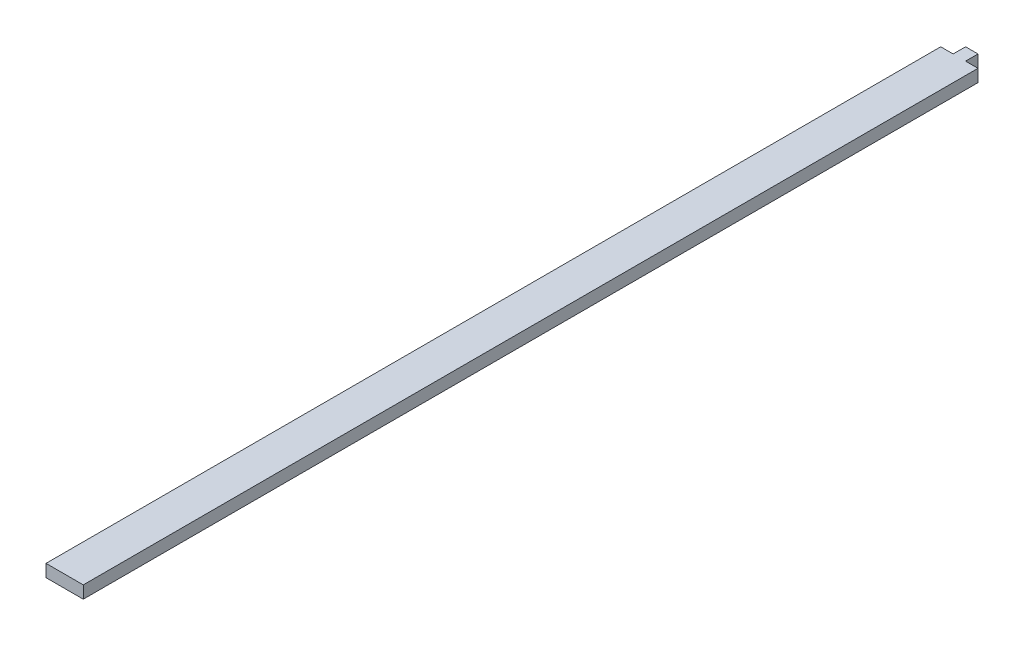
SolidWorks part; units mm, degrees
material "Mahogany"
ref_plane "Front" through (0, 0, 0) normal (0, 0, 1) x (1, 0, 0)
ref_plane "Top" through (0, 0, 0) normal (0, 1, 0) x (1, 0, 0)
ref_plane "Right" through (0, 0, 0) normal (1, 0, 0) x (0, 0, -1)
sketch "Sketch1" plane through (0, 0, 0) normal (0, 1, 0) x (1, 0, 0)
  line L1 (0, 0) -> (19.05, 0)
  line L2 (0, 0) -> (0, 457.2)
  line L3 (0, 457.2) -> (19.05, 457.2)
  line L4 (19.05, 0) -> (19.05, 457.2)
  line L5 (6.35, 457.2) -> (12.7, 457.2)
  line L6 (6.35, 457.2) -> (6.35, 463.55)
  line L7 (6.35, 463.55) -> (12.7, 463.55)
  line L8 (12.7, 457.2) -> (12.7, 463.55)
  point P9 (9.525, 463.55)
  point P10 (9.525, 457.2)
  dimension "D1" = 457.2
  dimension "D2" = 19.05
  dimension "D3" = 6.35
  dimension "D4" = 6.35
extrude "Boss-Extrude1" add sketch "Sketch1" along normal blind 6.35 contours L1 L4 L3 L2 | L3 L8 L7 L6
